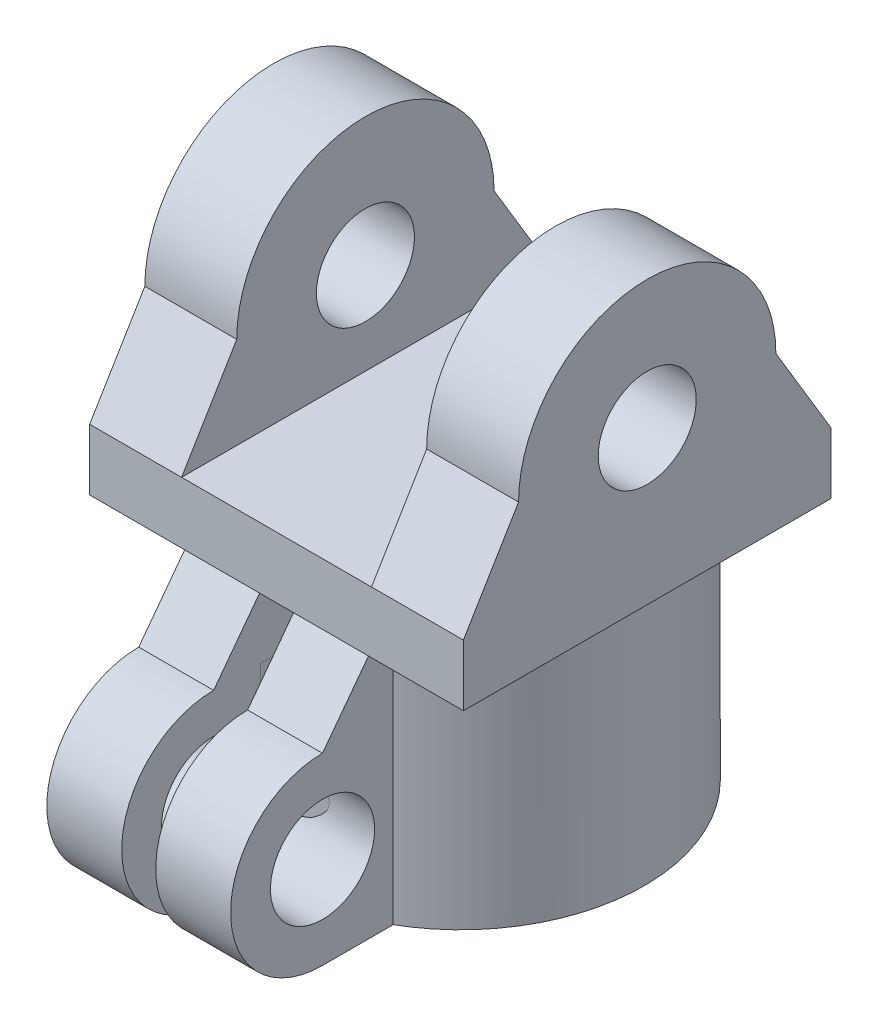
SolidWorks part; units mm, degrees
ref_plane "前视基准面" through (0, 0, 0) normal (0, 0, 1) x (1, 0, 0)
ref_plane "上视基准面" through (0, 0, 0) normal (0, 1, 0) x (1, 0, 0)
ref_plane "右视基准面" through (0, 0, 0) normal (1, 0, 0) x (0, 0, -1)
sketch "草图1" plane through (0, 0, 0) normal (0, 1, 0) x (1, 0, 0)
  circle A0 centre (0, 0) radius 4.2
  circle A1 centre (0, 0) radius 6
  dimension "D1" = 8.4
  dimension "D2" = 12
extrude "凸台-拉伸1" add sketch "草图1" along normal blind 8
sketch "草图2" plane through (0, 8, 0) normal (0, 1, 0) x (1, 0, 0)
  line L1 (-6.1, -6) -> (6.1, -6)
  line L2 (-6.1, -6) -> (-6.1, 6)
  line L3 (-6.1, 6) -> (6.1, 6)
  line L4 (6.1, -6) -> (6.1, 6)
  line L5 (-6.1, -6) -> (6.1, 6) construction
  line L6 (-6.1, 6) -> (6.1, -6) construction
  circle A0 centre (0, 0) radius 6 construction
  point P0 (0, 0)
  dimension "D1" = 12.2
extrude "凸台-拉伸2" add sketch "草图2" along normal blind 2
sketch "草图3" plane through (-6.1, 0, 0) normal (-1, 0, 0) x (0, 0, 1)
  line L3 (0, 20.2944) -> (0, -2.8579) construction
  line L4 (-6, 10) -> (6, 10)
  line L5 (-4.2, 13) -> (-6, 10)
  line L6 (4.2, 13) -> (6, 10)
  arc A0 (4.2, 13) -> (-4.2, 13) centre (0, 13) ccw
  circle A1 centre (0, 13) radius 1.6
  dimension "D2" = 8.4
extrude "凸台-拉伸3" add sketch "草图3" against normal blind 3
mirror "镜向1" about plane through (0, 0, 0) normal (1, 0, 0) of "凸台-拉伸2", "凸台-拉伸3"
sketch "草图4" plane through (0, 0, 0) normal (1, 0, 0) x (0, 0, -1)
  line L0 (3.8082, 3) -> (-10.8285, 3) construction
  line L6 (-5.5, 8.1815) -> (-5.5, -0.4327) construction
  line L7 (-6, 8) -> (0, 8)
  line L8 (-6, 8) -> (6, 8) construction
  line L9 (0, 8) -> (0, 0)
  line L10 (0, 0) -> (-7.5, 0)
  line L11 (-7.5, 6) -> (-6, 8)
  circle A2 centre (-7.5, 3) radius 1.7
  arc A3 (-7.5, 6) -> (-7.5, 0) centre (-7.5, 3) ccw
  dimension "D1" = 2
  dimension "D3" = 3
  dimension "D2" = 3.4
  dimension "D4" = 6
extrude "凸台-拉伸4" add sketch "草图4" along normal blind 3 and the other way blind 3 separate body
sketch "草图5" plane through (0, 0, 0) normal (0, -1, 0) x (1, 0, 0)
  circle A0 centre (0, 0) radius 4.2 construction
  circle A1 centre (0, 0) radius 4.2
extrude "切除-拉伸1" cut sketch "草图5" against normal blind 6
sketch "草图6" plane through (0, 0, 0) normal (0, 0, 1) x (1, 0, 0)
  line L0 (0, -1.3797) -> (0, 16.8476) construction
  line L8 (-6.1, 8) -> (0, 8) construction
  line L9 (-0.5547, 8) -> (-0.5547, 0)
  line L11 (0.5547, 8) -> (0.5547, 0)
  line L12 (-0.5547, 8) -> (0.5547, 8)
  line L13 (-0.5547, 0) -> (0.5547, 0)
  point P11 (0, 0)
  point P12 (0, 8)
  point P13 (0, 0)
  point P14 (0, 8)
extrude "切除-拉伸2" cut sketch "草图6" along normal through all
sketch "草图7" plane through (0, 10, 0) normal (0, 1, 0) x (1, 0, 0)
  line L0 (3.1, -6) -> (3.1, 6) construction
